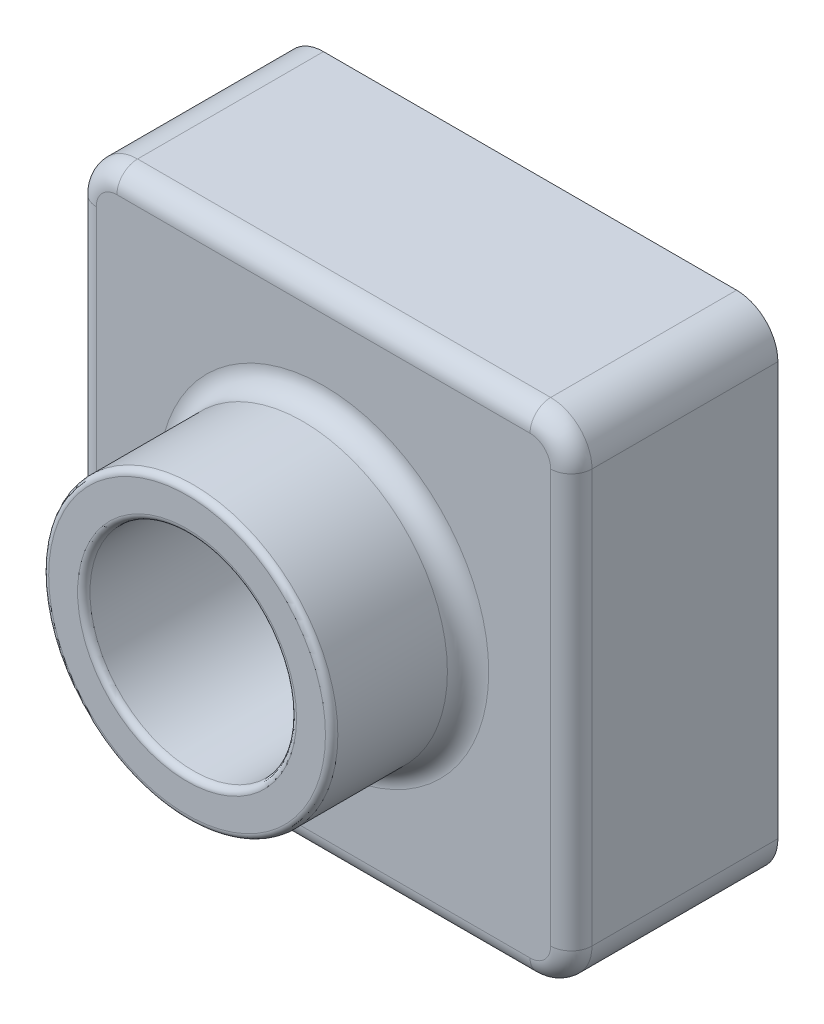
SolidWorks part; units mm, degrees
material "Chrome Stainless Steel"
ref_plane "Front" through (0, 0, 0) normal (0, 0, 1) x (1, 0, 0)
ref_plane "Top" through (0, 0, 0) normal (0, 1, 0) x (1, 0, 0)
ref_plane "Right" through (0, 0, 0) normal (1, 0, 0) x (0, 0, -1)
sketch "Sketch1" plane through (0, 0, 0) normal (0, 0, 1) x (1, 0, 0)
  line L1 (0, 0) -> (120, 0)
  line L2 (0, 0) -> (0, 120)
  line L3 (0, 120) -> (120, 120)
  line L4 (120, 0) -> (120, 120)
  dimension "D1" = 120
  dimension "D2" = 120
extrude "Boss-Extrude1" add sketch "Sketch1" along normal blind 50
sketch "Sketch2" plane through (0, 0, 50) normal (0, 0, 1) x (1, 0, 0)
  line L0 (120, 120) -> (0, 120) construction
  line L1 (120, 0) -> (120, 120) construction
  circle A0 centre (60, 60) radius 35
  point P2 (60, 120)
  dimension "D1" = 70
  dimension "D2" = 60
  dimension "D3" = 60
extrude "Boss-Extrude2" add sketch "Sketch2" along normal blind 33.02
sketch "Sketch3" plane through (0, 0, 83.02) normal (0, 0, 1) x (1, 0, 0)
  circle A0 centre (60, 60) radius 25
  dimension "D1" = 50
extrude "Cut-Extrude1" cut sketch "Sketch3" against normal through all
fillet "Fillet1" radius 10 4 edges at (0, 0, 25) (0, 120, 25) (120, 120, 25) (120, 0, 25)
fillet "Fillet2" radius 1.5 2 edges at (95, 60, 83.02) (85, 60, 83.02)
fillet "Fillet3" radius 5 9 edges at (2.9289, 117.0711, 50) (60, 120, 50) (117.0711, 117.0711, 50) (120, 60, 50) (117.0711, 2.9289, 50) (60, 0, 50) (2.9289, 2.9289, 50) (0, 60, 50) (25, 60, 50)
shell "Shell1" thickness 2
